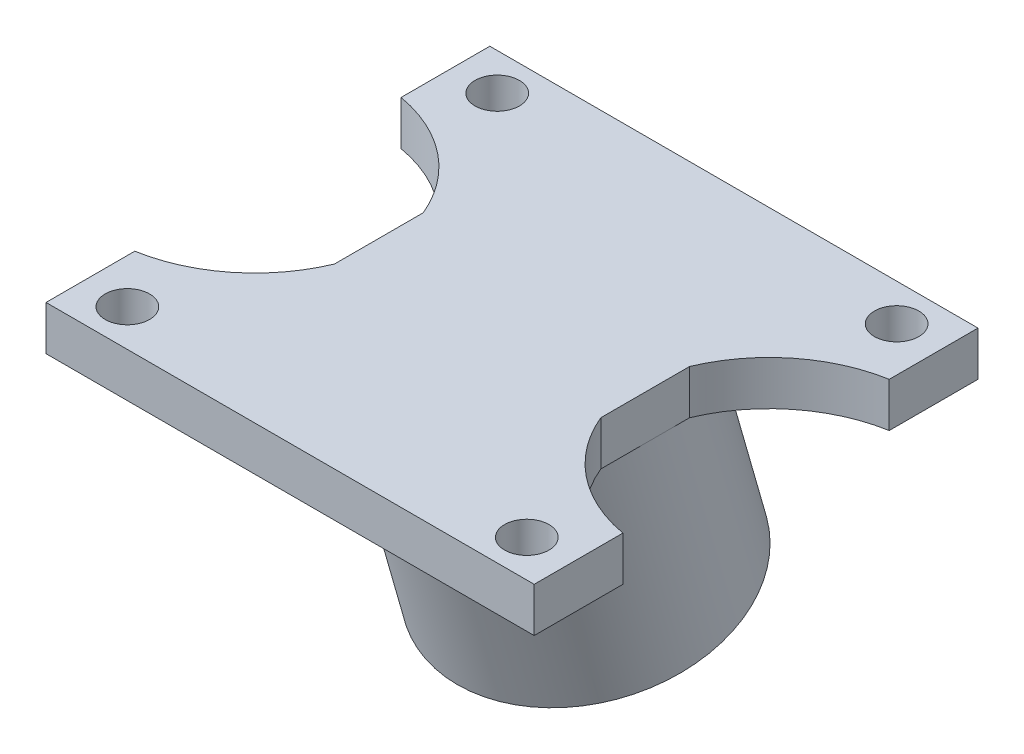
SolidWorks part; units mm, degrees
ref_plane "前视基准面" through (0, 0, 0) normal (0, 0, 1) x (1, 0, 0)
ref_plane "上视基准面" through (0, 0, 0) normal (0, 1, 0) x (1, 0, 0)
ref_plane "右视基准面" through (0, 0, 0) normal (1, 0, 0) x (0, 0, -1)
sketch "草图1" plane through (0, 0, 0) normal (0, 1, 0) x (1, 0, 0)
  line L0 (0, 0) -> (32.582, 0) construction
  line L1 (-16.5, 15) -> (16.5, 15)
  line L2 (-16.5, 15) -> (-16.5, 9)
  line L3 (-16.5, -15) -> (16.5, -15)
  line L4 (16.5, 15) -> (16.5, 9)
  line L5 (-16.5, 15) -> (16.5, -15) construction
  line L6 (-16.5, -15) -> (16.5, 15) construction
  line L7 (0, 0) -> (0, 26.7111) construction
  line L8 (9, 3) -> (9, -3)
  line L9 (-9, 3) -> (-9, -3)
  line L10 (16.5, -9) -> (16.5, -15)
  line L11 (-16.5, -9) -> (-16.5, -15)
  line L12 (0, 0) -> (-9, 0) construction
  circle A0 centre (-13.5, 12.5) radius 1.5
  circle A1 centre (13.5, 12.5) radius 1.5
  circle A2 centre (13.5, -12.5) radius 1.5
  circle A3 centre (-13.5, -12.5) radius 1.5
  arc A4 (9, 3) -> (16.5, 9) centre (18.2295, -0.8493) cw
  arc A5 (9, -3) -> (16.5, -9) centre (18.2295, 0.8493) ccw
  arc A6 (-9, 3) -> (-16.5, 9) centre (-18.2295, -0.8493) ccw
  arc A7 (-9, -3) -> (-16.5, -9) centre (-18.2295, 0.8493) cw
  point P0 (0, 0)
  dimension "D3" = 3
  dimension "D13" = 10
  dimension "D15" = 10
  dimension "D18" = 10
  dimension "D19" = 10
  dimension "D1" = 33
  dimension "D2" = 30
  dimension "D4" = 27
  dimension "D5" = 13.5
  dimension "D6" = 25
  dimension "D7" = 12.5
  dimension "D8" = 18
  dimension "D9" = 9
  dimension "D10" = 6
  dimension "D11" = 3
  dimension "D12" = 6
  dimension "D14" = 6
  dimension "D16" = 6
  dimension "D17" = 6
extrude "凸台-拉伸1" add sketch "草图1" along normal blind 3
sketch "草图2" plane through (0, 3, 0) normal (0, 1, 0) x (1, 0, 0)
  line L0 (-9, 0) -> (9, 0) construction
  line L1 (-9, 3) -> (-9, -3) construction
  line L2 (9, -3) -> (9, 3) construction
ref_plane "基准面4" through (0, 2.7721, 0.7949) normal (0, 0.9613, 0.2756) x (1, 0, 0)
sketch "草图3" plane through (0, 2.7721, 0.7949) normal (0, 0.9613, 0.2756) x (1, 0, 0)
  line L0 (-9, 0.8269) -> (9, 0.8269) construction
  line L1 (9, -2.0569) -> (9, 3.7107) construction
  circle A0 centre (0, 0.8269) radius 8
  circle A1 centre (0, 0.8269) radius 9
  dimension "D1" = 16
extrude "凸台-拉伸2" add sketch "草图3" against normal blind 18
sketch "草图4" plane through (0, 0, 15) normal (0, 0, 1) x (1, 0, 0)
  line L0 (9, 3) -> (9, 5.4807)
  line L1 (9, 5.4807) -> (-9, 5.4807)
  line L2 (-9, 5.4807) -> (-9, 3)
  line L3 (-9, 3) -> (9, 3)
  ellipse E0 centre (0, 3) end of major axis (9, 3) minor radius 2.4807 (9, 3) -> (-9, 3) ccw construction
extrude "切除-拉伸1" cut sketch "草图4" against normal blind 30
